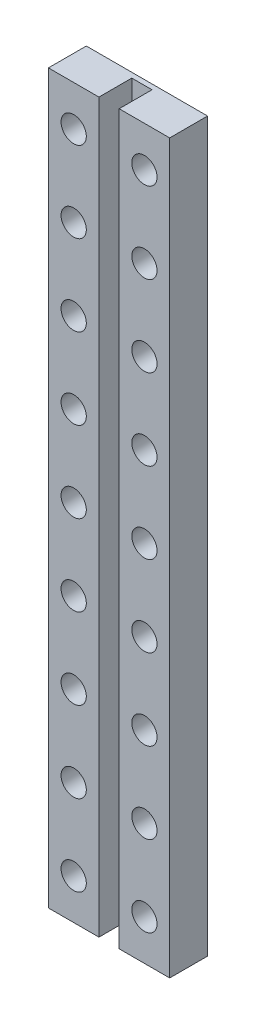
SolidWorks part; units mm, degrees
ref_plane "Plan de face" through (0, 0, 0) normal (0, 0, 1) x (1, 0, 0)
ref_plane "Plan de dessus" through (0, 0, 0) normal (0, 1, 0) x (1, 0, 0)
ref_plane "Plan de droite" through (0, 0, 0) normal (1, 0, 0) x (0, 0, -1)
sketch "Esquisse1" plane through (0, 0, 0) normal (0, 1, 0) x (1, 0, 0)
  line L0 (-2, -3.75) -> (-2, 2.75)
  line L1 (12, 3.75) -> (-12, 3.75)
  line L2 (12, 3.75) -> (12, -3.75)
  line L3 (12, -3.75) -> (2, -3.75)
  line L4 (-12, 3.75) -> (-12, -3.75)
  line L5 (12, 3.75) -> (-12, -3.75) construction
  line L6 (12, -3.75) -> (-12, 3.75) construction
  line L7 (-2, 2.75) -> (2, 2.75)
  line L8 (2, 2.75) -> (2, -3.75)
  line L9 (-2, 2.75) -> (2, -3.75) construction
  line L10 (0, 1.5046) -> (0, -2.3161) construction
  line L11 (-2, -3.75) -> (-12, -3.75)
  point P0 (0, 0)
  point P8 (0, -0.5)
  dimension "D1" = 7.5
  dimension "D2" = 24
  dimension "D3" = 1
  dimension "D4" = 10
extrude "BASE" add sketch "Esquisse1" against normal blind 144
sketch "Esquisse2" plane through (0, 0, 3.75) normal (0, 0, 1) x (1, 0, 0)
  line L0 (-7, 0) -> (-7, -38.4741) construction
  line L1 (-12, 0) -> (-2, 0) construction
  line L2 (-7, -5.5) -> (-4.873, -5.5) construction
  circle A0 centre (-7, -8) radius 2.5
  circle A1 centre (7, -8) radius 2.5
  circle A2 centre (7, -24) radius 2.5
  circle A3 centre (7, -40) radius 2.5
  circle A4 centre (7, -56) radius 2.5
  circle A5 centre (7, -72) radius 2.5
  circle A6 centre (7, -88) radius 2.5
  circle A7 centre (7, -104) radius 2.5
  circle A8 centre (7, -120) radius 2.5
  circle A9 centre (7, -136) radius 2.5
  circle A11 centre (-7, -24) radius 2.5
  circle A12 centre (-7, -40) radius 2.5
  circle A13 centre (-7, -56) radius 2.5
  circle A14 centre (-7, -72) radius 2.5
  circle A15 centre (-7, -88) radius 2.5
  circle A16 centre (-7, -104) radius 2.5
  circle A17 centre (-7, -120) radius 2.5
  circle A18 centre (-7, -136) radius 2.5
  dimension "D2" = 5
  dimension "D1" = 5.5
  dimension "D3" = 2
  dimension "D4" = 9
extrude "TROU" cut sketch "Esquisse2" against normal through all
